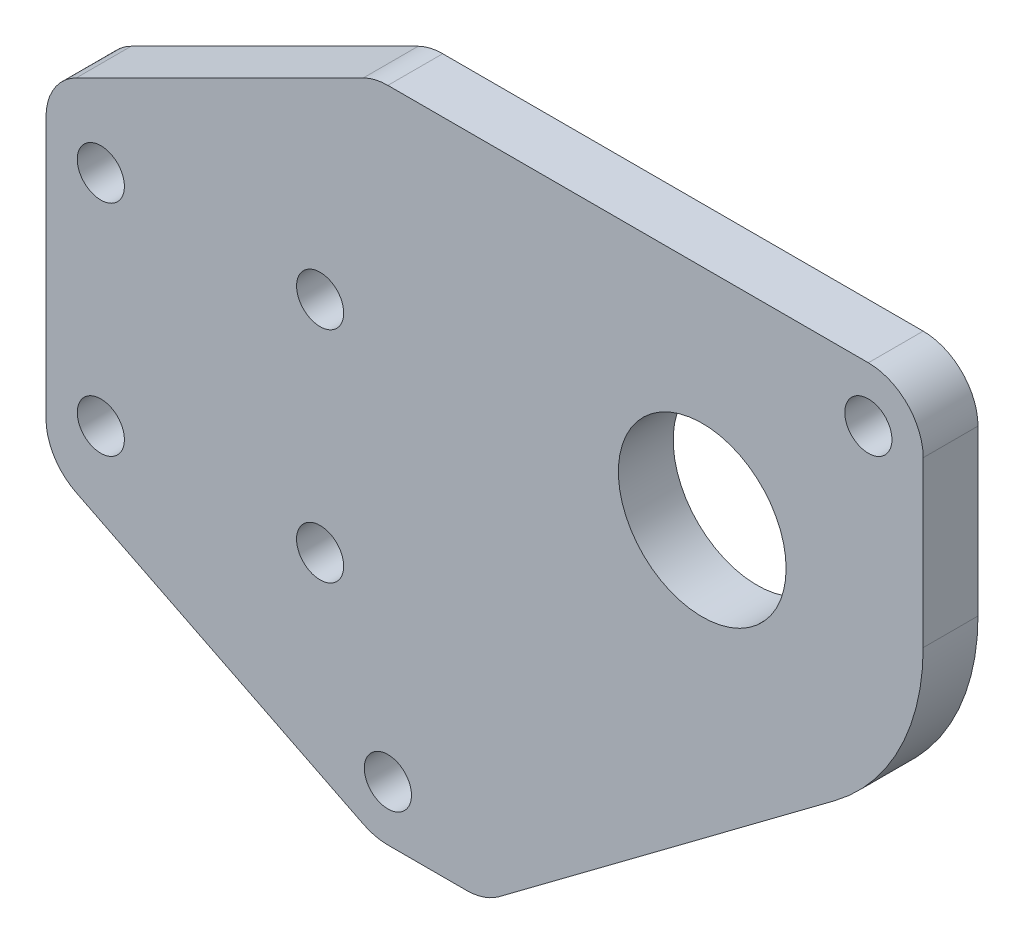
SolidWorks part; units mm, degrees
material "ﾎﾟﾘｴﾁﾚﾝｲﾐﾝ(PEI)"
ref_plane "正面" through (0, 0, 0) normal (0, 0, 1) x (1, 0, 0)
ref_plane "平面" through (0, 0, 0) normal (0, 1, 0) x (1, 0, 0)
ref_plane "右側面" through (0, 0, 0) normal (1, 0, 0) x (0, 0, -1)
sketch "ｽｹｯﾁ1" plane through (0, 0, 0) normal (0, 0, 1) x (1, 0, 0)
  line L0 (0, 24.75) -> (0, -24.75) construction
  line L1 (-5, 24.75) -> (5, 24.75) construction
  line L2 (-5, 24.75) -> (-5, -24.75) construction
  line L3 (-5, -24.75) -> (5, -24.75) construction
  line L4 (5, 24.75) -> (5, -24.75) construction
  line L5 (-5, 24.75) -> (5, -24.75) construction
  line L6 (-5, -24.75) -> (5, 24.75) construction
  line L7 (-5, 0) -> (5, 0) construction
  line L8 (0.65, -27.15) -> (0.65, -20.15)
  line L9 (-10.15, 20.15) -> (10.15, 20.15)
  line L10 (-10.15, 20.15) -> (-10.15, -20.15)
  line L11 (-10.15, -20.15) -> (10.15, -20.15)
  line L12 (10.15, 20.15) -> (10.15, -20.15)
  line L13 (-10.15, 20.15) -> (10.15, -20.15) construction
  line L14 (-10.15, -20.15) -> (10.15, 20.15) construction
  line L15 (-0.65, 27.15) -> (0.65, 27.15)
  line L16 (-0.65, 27.15) -> (-0.65, 20.15)
  line L17 (-0.65, 20.15) -> (0.65, 20.15)
  line L18 (0.65, 27.15) -> (0.65, 20.15)
  line L19 (-0.65, 27.15) -> (0.65, 20.15) construction
  line L20 (-0.65, 20.15) -> (0.65, 27.15) construction
  line L21 (-0.65, -27.15) -> (-0.65, -20.15)
  line L22 (-0.65, -27.15) -> (0.65, -27.15)
  line L23 (10.15, 0) -> (-51.75, 0) construction
  line L25 (-59.85, 30) -> (20.15, 30)
  line L26 (-59.85, 30) -> (-59.85, -30)
  line L27 (-59.85, -30) -> (20.15, -30)
  line L28 (20.15, 30) -> (20.15, -30)
  line L29 (-59.85, 30) -> (20.15, -30) construction
  line L30 (-59.85, -30) -> (20.15, 30) construction
  circle A0 centre (-5, 24.75) radius 2.15
  circle A1 centre (5, 24.75) radius 2.15
  circle A2 centre (5, -24.75) radius 2.15
  circle A3 centre (-5, -24.75) radius 2.15
  circle A4 centre (0, 10) radius 7.65
  point P0 (0, 0)
  point P14 (0, 0)
  point P19 (0, 23.65)
  point P29 (-19.85, 0)
  dimension "D3" = 4.3
  dimension "D11" = 15.3
  dimension "D1" = 10
  dimension "D2" = 49.5
  dimension "D4" = 20.3
  dimension "D5" = 40.3
  dimension "D6" = 1.3
  dimension "D7" = 7
  dimension "D8" = 60
  dimension "D9" = 10
  dimension "D10" = 80
  dimension "D12" = 20
extrude "ﾎﾞｽ - 押し出し1" add sketch "ｽｹｯﾁ1" along normal blind 5 contours L28 L25 L26 L27 A1 A0 L22 L21 L11 L10 L9 L16 L15 L18 L12 L8 A2 A3 | L12 L9 L10 L11 | A3 | L21 L22 L8 L11 | A2 | A0 | A1 | L18 L15 L16 L9
sketch "ｽｹｯﾁ2" plane through (0, 0, 5) normal (0, 0, 1) x (1, 0, 0)
  line L0 (-59.85, 0) -> (20.15, 0) construction
  line L1 (-59.85, 30) -> (-59.85, -30) construction
  line L2 (20.15, 30) -> (20.15, -30) construction
  line L3 (-54.85, 0) -> (-54.85, 10) construction
  line L4 (-54.85, 10) -> (-34.85, 10) construction
  circle A0 centre (-54.85, 10) radius 2.15
  circle A1 centre (-54.85, -10) radius 2.15
  circle A2 centre (-34.85, 10) radius 2.15
  circle A3 centre (-34.85, -10) radius 2.15
  dimension "D1" = 4.3
  dimension "D2" = 5
  dimension "D3" = 20
  dimension "D5" = 20
  dimension "D4" = 2
extrude "ｶｯﾄ - 押し出し1" cut sketch "ｽｹｯﾁ2" against normal through all
sketch "ｽｹｯﾁ3" plane through (0, 0, 5) normal (0, 0, 1) x (1, 0, 0)
  line L0 (-59.85, 30) -> (20.15, 30) construction
  line L1 (20.15, 30) -> (20.15, -30) construction
  line L6 (20.15, -30) -> (20.15, 30)
  line L7 (20.15, 30) -> (-59.85, 30)
  line L8 (-59.85, 30) -> (-59.85, -30)
  line L9 (-59.85, -30) -> (20.15, -30)
  line L10 (20.15, -30) -> (20.15, 30)
  line L11 (20.15, 30) -> (-59.85, 30)
  line L12 (-59.85, 30) -> (-59.85, -30)
  line L13 (-59.85, -30) -> (20.15, -30)
  circle A0 centre (15.15, 25) radius 5
  circle A1 centre (15.15, 25) radius 2.15
  line M12 (20.15, 30) -> (-59.85, 30)
  dimension "D1" = 10
  dimension "D2" = 4.3
  dimension "D3" = 0
extrude "ｶｯﾄ - 押し出し2" cut sketch "ｽｹｯﾁ3" against normal through all contours A1 | A0 L10 M12
sketch "ｽｹｯﾁ4" plane through (0, 0, 5) normal (0, 0, 1) x (1, 0, 0)
  line L0 (-59.85, 0) -> (20.15, 0) construction
  line L1 (-59.85, 30) -> (-59.85, -30) construction
  line L2 (20.15, 25) -> (20.15, -30) construction
  line L3 (-59.85, 15) -> (-29.85, 30)
  line L4 (-59.85, 30) -> (15.15, 30) construction
  line L5 (-59.85, -15) -> (-29.85, -30)
  line L6 (12.0657, -6.1382) -> (-19.85, -30)
  line L10 (20.15, -30) -> (20.15, 25)
  line L11 (15.15, 30) -> (-59.85, 30)
  line L12 (-59.85, 30) -> (-59.85, -30)
  line L13 (-59.85, -30) -> (20.15, -30)
  line L14 (20.15, -30) -> (20.15, 25)
  line L15 (15.15, 30) -> (-59.85, 30)
  line L16 (-59.85, 30) -> (-59.85, -30)
  line L17 (-59.85, -30) -> (20.15, -30)
  circle A0 centre (0, 10) radius 7.65 construction
  arc A1 (20.15, 25) -> (15.15, 30) centre (15.15, 25) ccw
  arc A2 (20.15, 25) -> (15.15, 30) centre (15.15, 25) ccw
  circle A3 centre (0, 10) radius 7.65
  circle A4 centre (0, 10) radius 20.15
  line M15 (20.15, -30) -> (20.15, 25)
  line M17 (15.15, 30) -> (-59.85, 30)
  line M18 (-59.85, 30) -> (-59.85, -30)
  line M19 (-59.85, -30) -> (20.15, -30)
  dimension "D4" = 40
  dimension "D1" = 30
  dimension "D2" = 30
  dimension "D3" = 0
extrude "ｶｯﾄ - 押し出し3" cut sketch "ｽｹｯﾁ4" against normal through all contours L3 M18 M17 | L5 M18 M19 | L0 A4 L6 M19 M15 | A4 L0 L14
sketch "ｽｹｯﾁ6" plane through (0, 0, 5) normal (0, 0, 1) x (1, 0, 0)
  line L0 (-59.85, -15) -> (-29.85, -30) construction
  line L1 (-29.85, -30) -> (-19.85, -30) construction
  circle A0 centre (-28.6697, -25) radius 5 construction
  circle A1 centre (-28.6697, -25) radius 2.15
  dimension "D1" = 10
  dimension "D2" = 4.3
extrude "ｶｯﾄ - 押し出し5" cut sketch "ｽｹｯﾁ6" against normal through all
fillet "ﾌｨﾚｯﾄ1" radius 5 5 edges at (-19.85, -30, 2.5) (-29.85, -30, 2.5) (-59.85, -15, 2.5) (-59.85, 15, 2.5) (-29.85, 30, 2.5)
